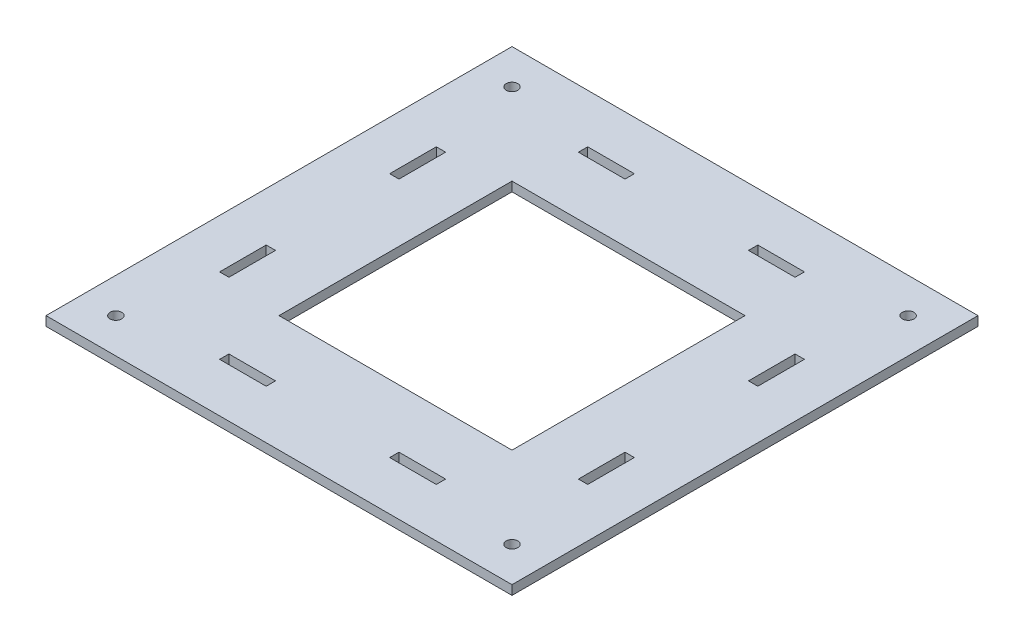
SolidWorks part; units mm, degrees
ref_plane "Alzado" through (0, 0, 0) normal (0, 0, 1) x (1, 0, 0)
ref_plane "Planta" through (0, 0, 0) normal (0, 1, 0) x (1, 0, 0)
ref_plane "Vista lateral" through (0, 0, 0) normal (1, 0, 0) x (0, 0, -1)
sketch "Croquis1" plane through (0, 0, 0) normal (0, 1, 0) x (1, 0, 0)
  line L0 (100, 15) -> (100, 0) construction
  line L1 (0, 0) -> (200, 0)
  line L2 (0, 0) -> (0, 200)
  line L3 (0, 200) -> (200, 200)
  line L4 (200, 0) -> (200, 200)
  line L5 (15, 15) -> (185, 15) construction
  line L6 (15, 15) -> (15, 185) construction
  line L7 (15, 185) -> (185, 185) construction
  line L8 (185, 15) -> (185, 185) construction
  line L9 (185, 100) -> (200, 100) construction
  circle A0 centre (15, 185) radius 2.5
  circle A1 centre (185, 185) radius 2.5
  circle A2 centre (185, 15) radius 2.5
  circle A3 centre (15, 15) radius 2.5
  dimension "D3" = 5
  dimension "D1" = 200
  dimension "D2" = 170
extrude "Saliente-Extruir1" add sketch "Croquis1" along normal blind 4
sketch "Croquis2" plane through (0, 4, 0) normal (0, 1, 0) x (1, 0, 0)
  line L0 (25, 100) -> (0, 100) construction
  line L1 (25, 25) -> (175, 25)
  line L2 (25, 25) -> (25, 175)
  line L3 (25, 175) -> (175, 175)
  line L4 (175, 25) -> (175, 175)
  line L5 (0, 200) -> (0, 0) construction
  line L6 (100, 25) -> (100, 0) construction
  line L7 (0, 0) -> (200, 0) construction
  line L8 (25, 100) -> (175, 100) construction
  line L9 (100, 175) -> (100, 25) construction
  line L10 (23, 126.5) -> (23, 100) construction
  line L19 (25, 25) -> (175, 25) construction
  line L20 (25, 25) -> (25, 175) construction
  line L21 (25, 175) -> (175, 175) construction
  line L22 (175, 25) -> (175, 175) construction
  line L23 (25, 126.5) -> (21, 126.5)
  line L24 (25, 126.5) -> (25, 146.5)
  line L25 (25, 146.5) -> (21, 146.5)
  line L26 (21, 126.5) -> (21, 146.5)
  line L27 (59.9079, 100) -> (59.9079, 175) construction
  line L28 (25, 136.5) -> (59.9079, 136.5) construction
  line L29 (25, 150.0904) -> (100, 150.0904) construction
  line L30 (63.5, 175) -> (63.5, 150.0904) construction
  line L31 (53.5, 175) -> (73.5, 175)
  line L32 (53.5, 175) -> (53.5, 179)
  line L33 (53.5, 179) -> (73.5, 179)
  line L34 (73.5, 175) -> (73.5, 179)
  line L35 (175, 146.5) -> (179, 146.5)
  line L36 (175, 146.5) -> (175, 126.5)
  line L37 (175, 126.5) -> (179, 126.5)
  line L38 (179, 146.5) -> (179, 126.5)
  line L39 (126.5, 175) -> (146.5, 175)
  line L40 (126.5, 175) -> (126.5, 179)
  line L41 (126.5, 179) -> (146.5, 179)
  line L42 (146.5, 175) -> (146.5, 179)
  line L43 (146.5, 25) -> (146.5, 21)
  line L44 (146.5, 25) -> (126.5, 25)
  line L45 (126.5, 25) -> (126.5, 21)
  line L46 (146.5, 21) -> (126.5, 21)
  line L47 (175, 73.5) -> (175, 53.5)
  line L48 (175, 73.5) -> (179, 73.5)
  line L49 (179, 73.5) -> (179, 53.5)
  line L50 (175, 53.5) -> (179, 53.5)
  line L51 (25, 53.5) -> (21, 53.5)
  line L52 (25, 53.5) -> (25, 73.5)
  line L53 (25, 73.5) -> (21, 73.5)
  line L54 (21, 53.5) -> (21, 73.5)
  line L55 (73.5, 25) -> (53.5, 25)
  line L56 (73.5, 25) -> (73.5, 21)
  line L57 (73.5, 21) -> (53.5, 21)
  line L58 (53.5, 25) -> (53.5, 21)
  line L59 (63.5, 162.5452) -> (100, 162.5452) construction
  line L60 (42.454, 136.5) -> (42.454, 100) construction
  point P18 (25, 100)
  point P19 (100, 175)
  dimension "D1" = 150
  dimension "D2" = 150
  dimension "D3" = 4
  dimension "D4" = 4
  dimension "D5" = 20
  dimension "D6" = 36.5
extrude "Cortar-Extruir1" cut sketch "Croquis2" against normal blind 4 contours L32 L31 L34 L33 | L2 L1 L4 L3 | L43 L46 L45 L44 | L55 L58 L57 L56 | L47 L50 L49 L48 | L35 L38 L37 L36 | L51 L54 L53 L52 | L39 L42 L41 L40 | L24 L23 L26 L25
sketch "Croquis3" plane through (0, 4, 0) normal (0, 1, 0) x (1, 0, 0)
  line L0 (50, 150) -> (50, 50)
  line L1 (25, 175) -> (175, 175)
  line L2 (25, 175) -> (25, 25)
  line L3 (25, 25) -> (175, 25)
  line L4 (175, 175) -> (175, 25)
  line L5 (50, 50) -> (150, 50)
  line L6 (150, 150) -> (150, 50)
  line L7 (50, 150) -> (150, 150)
  dimension "D1" = 25
extrude "Saliente-Extruir2" add sketch "Croquis3" against normal up to surface (4 mm away) up to face at (100, 0, -100)
